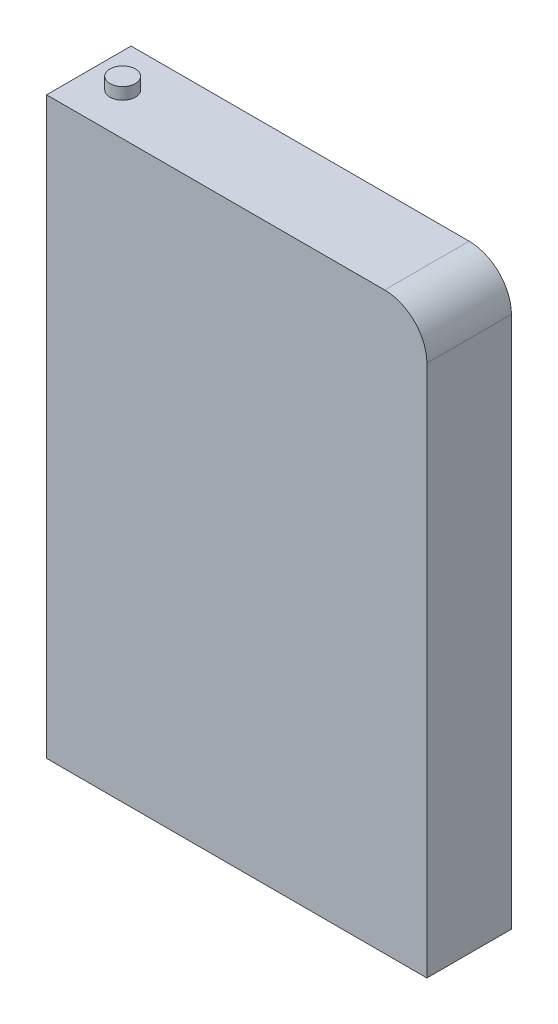
SolidWorks part; units mm, degrees
ref_plane "前视基准面" through (0, 0, 0) normal (0, 0, 1) x (1, 0, 0)
ref_plane "上视基准面" through (0, 0, 0) normal (0, 1, 0) x (1, 0, 0)
ref_plane "右视基准面" through (0, 0, 0) normal (1, 0, 0) x (0, 0, -1)
sketch "草图1" plane through (0, 0, 0) normal (0, 0, 1) x (1, 0, 0)
  line L1 (-22.5, -34) -> (22.5, -34)
  line L2 (-22.5, -34) -> (-22.5, 34)
  line L3 (-22.5, 34) -> (22.5, 34)
  line L4 (22.5, -34) -> (22.5, 34)
  line L5 (-22.5, -34) -> (22.5, 34) construction
  line L6 (-22.5, 34) -> (22.5, -34) construction
  point P0 (0, 0)
  dimension "D1" = 45
  dimension "D2" = 68
extrude "凸台-拉伸1" add sketch "草图1" along normal blind 10
fillet "圆角1" radius 5 1 edges at (22.5, 34, 5)
sketch "草图2" plane through (0, 34, 0) normal (0, 1, 0) x (1, 0, 0)
  line L0 (17.5, -10) -> (-22.5, -10) construction
  line L1 (-22.5, -10) -> (-22.5, 0) construction
  circle A0 centre (-18.5, -5) radius 1.5
  dimension "D1" = 3
  dimension "D2" = 5
  dimension "D3" = 4
extrude "凸台-拉伸2" add sketch "草图2" along normal blind 1.4
sketch "草图3" plane through (0, -34, 0) normal (0, -1, 0) x (1, 0, 0)
  line L4 (-22.5, 0) -> (22.5, 0)
  line L5 (22.5, 0) -> (22.5, 10)
  line L6 (22.5, 10) -> (-22.5, 10)
  line L7 (-22.5, 10) -> (-22.5, 0)
  line L8 (-22.5, 0) -> (22.5, 0)
  line L9 (22.5, 0) -> (22.5, 10)
  line L10 (22.5, 10) -> (-22.5, 10)
  line L11 (-22.5, 10) -> (-22.5, 0)
  circle A1 centre (-18.5, 5) radius 2.5
  point P7 (0, 0)
  point P9 (-18.2448, 2.0094)
  dimension "D2" = 5
  dimension "D3" = 5
  dimension "D4" = 4
  dimension "D1" = 0
extrude "切除-拉伸1" cut sketch "草图3" against normal blind 5 flip side to cut
